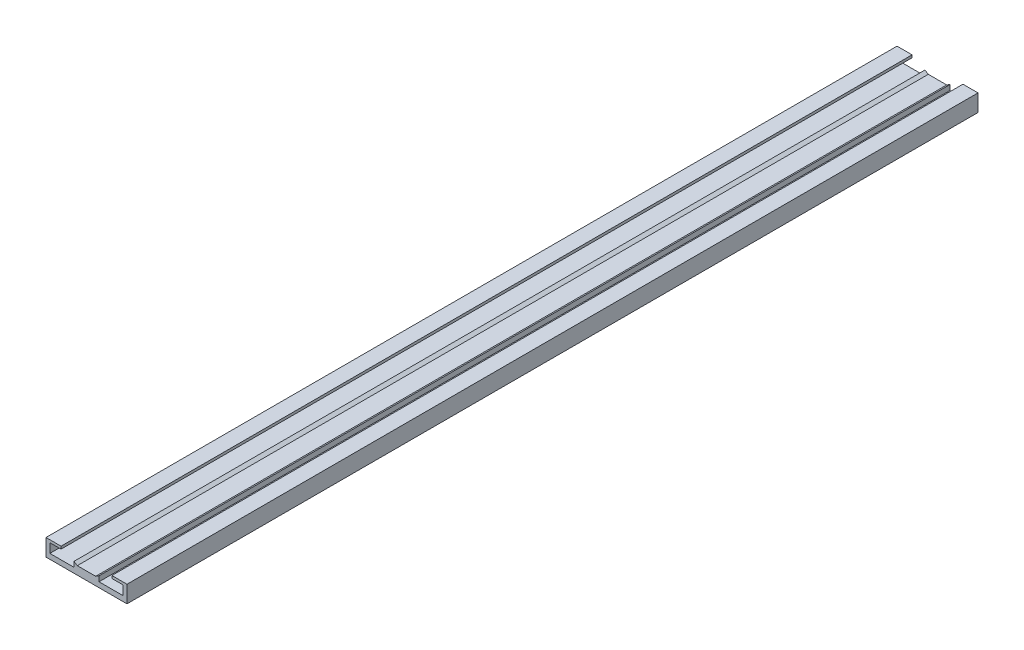
SolidWorks part; units mm, degrees
material "6061 Alloy"
ref_plane "Front Plane" through (0, 0, 0) normal (0, 0, 1) x (1, 0, 0)
ref_plane "Top Plane" through (0, 0, 0) normal (0, 1, 0) x (1, 0, 0)
ref_plane "Right Plane" through (0, 0, 0) normal (1, 0, 0) x (0, 0, -1)
sketch "Sketch1" plane through (0, 0, 0) normal (0, 0, 1) x (1, 0, 0)
  line L0 (0, 0) -> (19.939, 0)
  line L1 (0, 0) -> (-19.939, 0)
  line L2 (-19.939, 0) -> (-19.939, 8.382)
  line L3 (19.939, 0) -> (19.939, 8.382)
  line L4 (-19.939, 8.382) -> (-12.5222, 8.382)
  line L5 (19.939, 8.382) -> (12.5222, 8.382)
  line L6 (-12.5222, 8.382) -> (-12.5222, 7.112)
  line L7 (12.5222, 8.382) -> (12.5222, 7.112)
  line L8 (-18.034, 7.112) -> (-18.034, 2.54)
  line L9 (-18.034, 7.112) -> (-12.5222, 7.112)
  line L10 (18.034, 7.112) -> (18.034, 2.54)
  line L11 (12.5222, 7.112) -> (18.034, 7.112)
  line L12 (-18.034, 2.54) -> (-6.1722, 2.54)
  line L13 (18.034, 2.54) -> (6.1722, 2.54)
  line L14 (-6.1722, 2.54) -> (-6.1722, 5.08)
  line L15 (6.1722, 2.54) -> (6.1722, 5.08)
  line L16 (-6.1722, 5.08) -> (-4.5308, 4.064)
  line L17 (-4.5308, 4.064) -> (4.5308, 4.064)
  line L18 (4.5308, 4.064) -> (6.1722, 5.08)
  dimension "D1" = 19.939
  dimension "D2" = 19.939
  dimension "D3" = 8.382
  dimension "D4" = 8.382
  dimension "D5" = 7.4168
  dimension "D6" = 7.4168
  dimension "D7" = 1.27
  dimension "D8" = 1.905
  dimension "D9" = 1.905
  dimension "D10" = 2.54
  dimension "D11" = 2.54
  dimension "D12" = 11.8618
  dimension "D13" = 11.8618
  dimension "D14" = 2.54
  dimension "D15" = 2.54
  dimension "D16" = 1.016
  dimension "D17" = 1.9304
  dimension "D18" = 1.9304
extrude "Boss-Extrude1" add sketch "Sketch1" along normal blind 419.1
